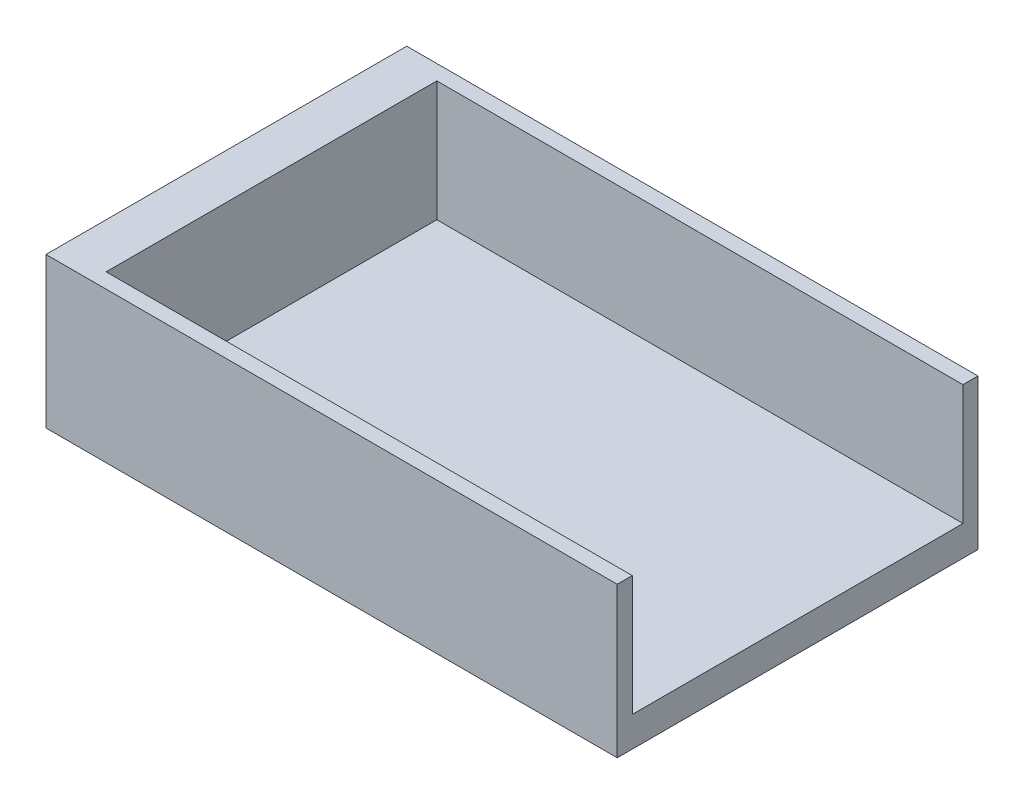
SolidWorks part; units mm, degrees
ref_plane "Front Plane" through (0, 0, 0) normal (0, 0, 1) x (1, 0, 0)
ref_plane "Top Plane" through (0, 0, 0) normal (0, 1, 0) x (1, 0, 0)
ref_plane "Right Plane" through (0, 0, 0) normal (1, 0, 0) x (0, 0, -1)
sketch "Sketch1" plane through (0, 0, 0) normal (0, 1, 0) x (1, 0, 0)
  line L1 (0, 0) -> (40, 0)
  line L2 (0, 0) -> (0, 24)
  line L3 (0, 24) -> (40, 24)
  line L4 (40, 0) -> (40, 24)
  dimension "D1" = 40
  dimension "D2" = 24
extrude "Boss-Extrude1" add sketch "Sketch1" along normal blind 2
sketch "Sketch2" plane through (0, 2, 0) normal (0, 1, 0) x (1, 0, 0)
  line L1 (3, 1) -> (39, 1)
  line L2 (3, 1) -> (3, 23)
  line L3 (3, 23) -> (39, 23)
  line L4 (39, 1) -> (39, 23)
  line L5 (0, 24) -> (40, 24)
  line L6 (0, 24) -> (0, 0)
  line L7 (0, 0) -> (40, 0)
  line L8 (40, 24) -> (40, 0)
  dimension "D1" = 22
  dimension "D2" = 36
  dimension "D3" = 1
  dimension "D4" = 1
extrude "Boss-Extrude3" add sketch "Sketch2" along normal blind 8
sketch "Sketch5" plane through (0, 2, 0) normal (0, 1, 0) x (1, 0, 0)
  line L0 (3, 1) -> (39, 1) construction
  line L1 (4, 1) -> (8, 1)
  line L2 (4, 1) -> (4, 4)
  line L3 (4, 4) -> (8, 4)
  line L4 (8, 1) -> (8, 4)
  line L6 (3, 23) -> (3, 1) construction
  dimension "D1" = 1
  dimension "D2" = 4
  dimension "D3" = 3
extrude "Cut-Extrude1" cut sketch "Sketch5" against normal blind 2
sketch "Sketch6" plane through (40, 0, 0) normal (1, 0, 0) x (0, 0, -1)
  line L1 (0, 10) -> (24, 10)
  line L2 (0, 10) -> (0, 0)
  line L3 (0, 0) -> (24, 0)
  line L4 (24, 10) -> (24, 0)
extrude "Cut-Extrude2" cut sketch "Sketch6" against normal blind 2
sketch "Sketch7" plane through (0, 0, 0) normal (0, -1, 0) x (1, 0, 0)
  line L0 (0, -24) -> (0, 0) construction
  line L1 (1, -10.5) -> (2, -10.5)
  line L2 (1, -10.5) -> (1, -13.5)
  line L3 (1, -13.5) -> (2, -13.5)
  line L4 (2, -10.5) -> (2, -13.5)
  line L5 (38, -24) -> (0, -24) construction
  dimension "D1" = 3
  dimension "D2" = 1
  dimension "D3" = 1
  dimension "D4" = 10.5
